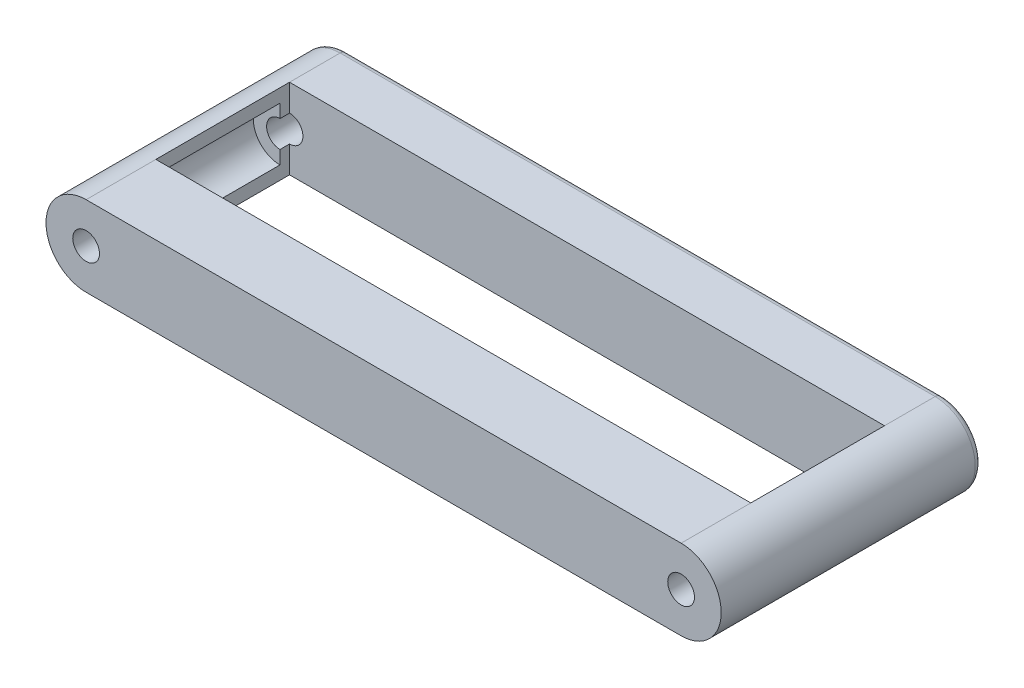
SolidWorks part; units mm, degrees
ref_plane "Alzado" through (0, 0, 0) normal (0, 0, 1) x (1, 0, 0)
ref_plane "Planta" through (0, 0, 0) normal (0, 1, 0) x (1, 0, 0)
ref_plane "Vista lateral" through (0, 0, 0) normal (1, 0, 0) x (0, 0, -1)
sketch "Croquis1" plane through (0, 0, 0) normal (0, 0, 1) x (1, 0, 0)
  line L0 (0, 0) -> (0, 15.795) construction
  line L1 (-44.5, 0) -> (44.5, 0) construction
  line L2 (-44.5, 6) -> (44.5, 6)
  line L3 (-44.5, -6) -> (44.5, -6)
  circle A0 centre (-44.5, 0) radius 2
  circle A1 centre (44.5, 0) radius 2
  arc A2 (-44.5, 6) -> (-44.5, -6) centre (-44.5, 0) ccw
  arc A3 (44.5, -6) -> (44.5, 6) centre (44.5, 0) ccw
  point P8 (0, 0)
  dimension "D1" = 4
  dimension "D3" = 6
  dimension "D2" = 44.5
extrude "Saliente-Extruir1" add sketch "Croquis1" along normal blind 39
sketch "Croquis2" plane through (0, 6, 0) normal (0, 1, 0) x (1, 0, 0)
  line L0 (-44.5, -39) -> (-44.5, 0) construction
  line L1 (-44.5, -8.5716) -> (44.5, -8.5716)
  line L2 (-44.5, -8.5716) -> (-44.5, -28.5716)
  line L3 (-44.5, -28.5716) -> (44.5, -28.5716)
  line L4 (44.5, -8.5716) -> (44.5, -28.5716)
  line L5 (44.5, -39) -> (44.5, 0) construction
  dimension "D1" = 20
extrude "Cortar-Extruir1" cut sketch "Croquis2" against normal blind 39
sketch "Croquis4" plane through (0, 0, 39) normal (0, 0, 1) x (1, 0, 0)
  line L0 (0, 0) -> (0, 21.2371) construction
  circle A0 centre (44.5, 0) radius 4
  circle A1 centre (-44.5, 0) radius 4
  point P6 (0, 20.503)
  point P7 (0, 21.2371)
  dimension "D1" = 8
extrude "Cortar-Extruir2" cut sketch "Croquis4" against normal blind 24 from offset 5 offset against normal yes
fillet "Redondeo1" radius 1 6 edges at (42.5, 0, 0) (-42.5, 0, 0) (0, -6, 0) (50.5, 0, 0) (0, 6, 0) (-50.5, 0, 0)
